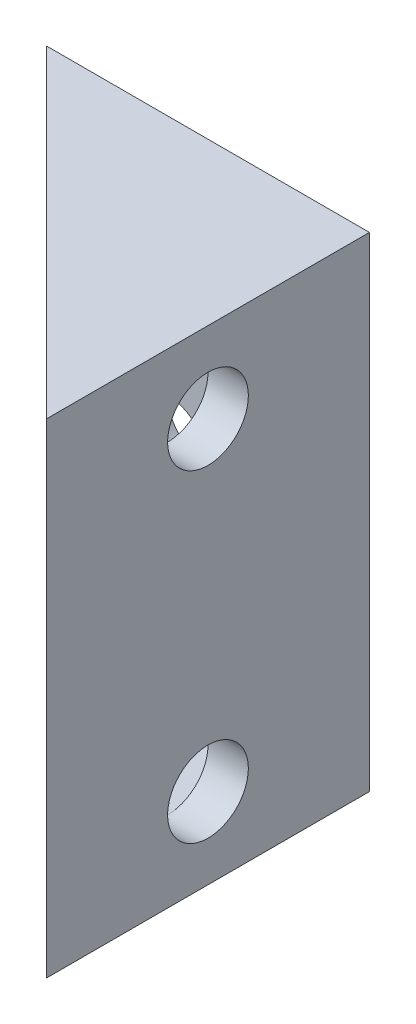
SolidWorks part; units mm, degrees
ref_plane "Front Plane" through (0, 0, 0) normal (0, 0, 1) x (1, 0, 0)
ref_plane "Top Plane" through (0, 0, 0) normal (0, 1, 0) x (1, 0, 0)
ref_plane "Right Plane" through (0, 0, 0) normal (1, 0, 0) x (0, 0, -1)
sketch "Sketch1" plane through (0, 0, 0) normal (0, 1, 0) x (1, 0, 0)
  line L1 (-12.7, -12.7) -> (12.7, -12.7)
  line L2 (-12.7, -12.7) -> (-12.7, 12.7)
  line L3 (-12.7, 12.7) -> (12.7, 12.7)
  line L4 (12.7, -12.7) -> (12.7, 12.7)
  line L5 (-12.7, -12.7) -> (12.7, 12.7) construction
  line L6 (-12.7, 12.7) -> (12.7, -12.7) construction
  point P0 (0, 0)
  dimension "D1" = 25.4
  dimension "D2" = 25.4
extrude "Boss-Extrude1" add sketch "Sketch1" along normal blind 38.1
sketch "Sketch2" plane through (0, 38.1, 0) normal (0, 1, 0) x (1, 0, 0)
  line L0 (-12.7, 12.7) -> (12.7, -12.7)
  line L1 (12.7, -12.7) -> (-12.7, -12.7)
  line L2 (-12.7, -12.7) -> (-12.7, 12.7)
extrude "Cut-Extrude1" cut sketch "Sketch2" against normal through all
sketch "Sketch3" plane through (0, 38.1, 0) normal (0, 1, 0) x (1, 0, 0)
  line L0 (-9.525, 9.525) -> (9.525, 9.525)
  line L1 (12.7, -12.7) -> (-12.7, 12.7) construction
  line L2 (9.525, 9.525) -> (9.525, -9.525)
  line L3 (9.525, -9.525) -> (-9.525, 9.525)
  line L4 (12.7, -12.7) -> (12.7, 12.7) construction
  line L5 (12.7, 12.7) -> (-12.7, 12.7) construction
  point P4 (8.5225, -8.5225)
  dimension "D1" = 3.175
  dimension "D2" = 3.175
extrude "Cut-Extrude2" cut sketch "Sketch3" along direction (0, -1, 0) on the side against the normal offset from surface (31.75 mm away) 3.175 from offset 3.175 offset against normal yes
sketch "Sketch4" plane through (0, 0, -12.7) normal (0, 0, -1) x (-1, 0, 0)
  line L0 (0, 0) -> (0, 38.1) construction
  line L1 (-12.7, 38.1) -> (12.7, 38.1) construction
  circle A0 centre (0, 19.05) radius 3.175
  dimension "D1" = 6.35
extrude "Cut-Extrude3" cut sketch "Sketch4" against normal through all
sketch "Sketch5" plane through (12.7, 0, 0) normal (1, 0, 0) x (0, 0, -1)
  line L0 (0, 0) -> (0, 38.1) construction
  line L1 (-12.7, 38.1) -> (12.7, 38.1) construction
  circle A0 centre (0, 31.75) radius 3.175
  circle A1 centre (0, 6.35) radius 3.175
  point P9 (0, 0)
  point P10 (0, 19.05)
  dimension "D2" = 6.35
  dimension "D3" = 6.35
  dimension "D1" = 25.4
  dimension "D4" = 12.7
extrude "Cut-Extrude5" cut sketch "Sketch5" against normal through all
